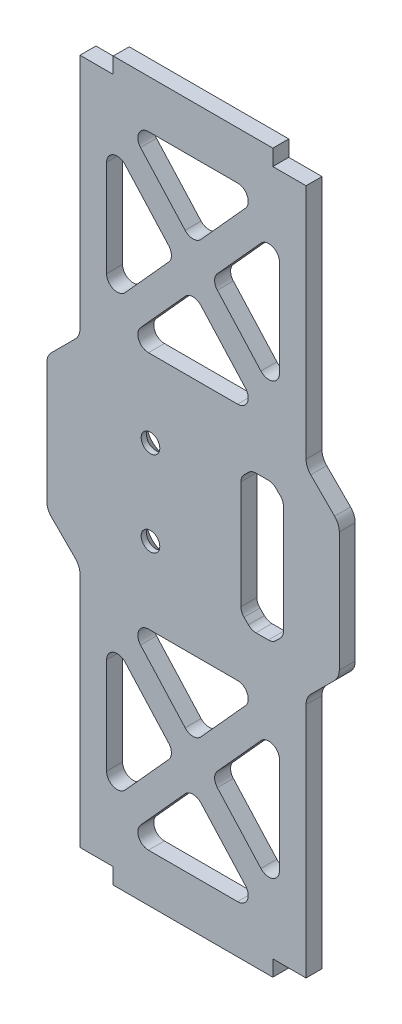
SolidWorks part; units mm, degrees
material "ABS"
ref_plane "Спереди" through (0, 0, 0) normal (0, 0, 1) x (1, 0, 0)
ref_plane "Сверху" through (0, 0, 0) normal (0, 1, 0) x (1, 0, 0)
ref_plane "Справа" through (0, 0, 0) normal (1, 0, 0) x (0, 0, -1)
sketch "Эскиз1" plane through (0, 0, 0) normal (0, 0, 1) x (1, 0, 0)
  line L0 (-27.5, 0) -> (27.5, 0) construction
  line L1 (-27.5, -64.5) -> (27.5, -64.5)
  line L2 (-27.5, -64.5) -> (-27.5, 64.5)
  line L3 (-27.5, 64.5) -> (27.5, 64.5)
  line L4 (27.5, -64.5) -> (27.5, 64.5)
  line L5 (-27.5, -64.5) -> (27.5, 64.5) construction
  line L6 (-27.5, 64.5) -> (27.5, -64.5) construction
  line L7 (-15, 61.5) -> (15, 61.5)
  line L8 (-15, 61.5) -> (-15, 67.5)
  line L9 (-15, 67.5) -> (15, 67.5)
  line L10 (15, 61.5) -> (15, 67.5)
  line L11 (-15, 61.5) -> (15, 67.5) construction
  line L12 (-15, 67.5) -> (15, 61.5) construction
  line L13 (-15, -67.5) -> (15, -61.5) construction
  line L14 (-15, -61.5) -> (15, -67.5) construction
  line L15 (15, -61.5) -> (15, -67.5)
  line L16 (-15, -67.5) -> (15, -67.5)
  line L17 (-15, -61.5) -> (-15, -67.5)
  line L18 (-15, -61.5) -> (15, -61.5)
  point P0 (0, 0)
  point P6 (0, 64.5)
  point P17 (0, -64.5)
  dimension "D1" = 3
  dimension "D2" = 30
  dimension "D3" = 12.5
  dimension "D4" = 129
extrude "Бобышка-Вытянуть1" add sketch "Эскиз1" along normal blind 3 contours L10 L7 L8 L3 L2 L1 L4 | L7 L10 L3 L8 | L3 L10 L9 L8 | L18 L17 L1 L15 | L1 L17 L16 L15
sketch "Эскиз2" plane through (0, 0, 3) normal (0, 0, 1) x (1, 0, 0)
  line L0 (-8, -64.5) -> (-8, 48.9753) construction
  line L1 (-27.5, -64.5) -> (-15, -64.5) construction
  line L2 (0, 0) -> (-27.5, 0) construction
  line L3 (-27.5, -64.5) -> (-27.5, 64.5) construction
  circle A0 centre (-8, 8) radius 1.75
  circle A1 centre (-8, -8) radius 1.75
  dimension "D1" = 3.5
  dimension "D2" = 8
  dimension "D3" = 8
extrude "Вырез-Вытянуть1" cut sketch "Эскиз2" against normal blind 10
sketch "Эскиз3" plane through (0, 0, 3) normal (0, 0, 1) x (1, 0, 0)
  line L0 (-21.25, 64.5) -> (-21.25, 18.75)
  line L1 (-27.5, 64.5) -> (-15, 64.5) construction
  line L2 (-21.25, 18.75) -> (-27.5, 12.5)
  line L3 (-27.5, -64.5) -> (-27.5, 64.5) construction
  line L4 (-27.5, 0) -> (27.5, 0) construction
  line L5 (27.5, -64.5) -> (27.5, 64.5) construction
  line L6 (0, 67.5) -> (0, -67.5) construction
  line L7 (-15, 67.5) -> (15, 67.5) construction
  line L8 (-15, -67.5) -> (15, -67.5) construction
  line L9 (-21.25, 64.5) -> (-37.5319, 71.3874)
  line L10 (-37.5319, 71.3874) -> (-35.5629, 12.5)
  line L11 (-35.5629, 12.5) -> (-27.5, 12.5)
  line L12 (35.5629, 12.5) -> (27.5, 12.5)
  line L13 (37.5319, 71.3874) -> (35.5629, 12.5)
  line L14 (21.25, 64.5) -> (37.5319, 71.3874)
  line L15 (21.25, 18.75) -> (27.5, 12.5)
  line L16 (21.25, 64.5) -> (21.25, 18.75)
  line L17 (21.25, -64.5) -> (21.25, -18.75)
  line L18 (21.25, -18.75) -> (27.5, -12.5)
  line L19 (21.25, -64.5) -> (37.5319, -71.3874)
  line L20 (37.5319, -71.3874) -> (35.5629, -12.5)
  line L21 (35.5629, -12.5) -> (27.5, -12.5)
  line L22 (-35.5629, -12.5) -> (-27.5, -12.5)
  line L23 (-37.5319, -71.3874) -> (-35.5629, -12.5)
  line L24 (-21.25, -64.5) -> (-37.5319, -71.3874)
  line L25 (-21.25, -18.75) -> (-27.5, -12.5)
  line L26 (-21.25, -64.5) -> (-21.25, -18.75)
  dimension "D1" = 135
  dimension "D2" = 12.5
extrude "Вырез-Вытянуть2" cut sketch "Эскиз3" against normal blind 10
fillet "Скругление1" radius 3 8 edges at (-21.25, -18.75, 1.5) (-27.5, -12.5, 1.5) (-27.5, 12.5, 1.5) (-21.25, 18.75, 1.5) (27.5, 12.5, 1.5) (21.25, 18.75, 1.5) (27.5, -12.5, 1.5) (21.25, -18.75, 1.5)
chamfer "Фаска1" distance 2 angle 45 2 edges at (-6.25, -8, 0) (-6.25, 8, 0)
sketch "Эскиз4" plane through (0, 0, 3) normal (0, 0, 1) x (1, 0, 0)
  line L0 (27.5, 0) -> (-27.5, 0) construction
  line L1 (27.5, -11.2574) -> (27.5, 11.2574) construction
  line L2 (-27.5, -11.2574) -> (-27.5, 11.2574) construction
  line L3 (0, 67.5) -> (0, -67.5) construction
  line L4 (-15, 67.5) -> (15, 67.5) construction
  line L5 (-15, -67.5) -> (15, -67.5) construction
  line L6 (-21.25, 19.9926) -> (-21.25, 64.5) construction
  line L7 (-16.25, 58.5) -> (16.25, 58.5)
  line L8 (-16.25, 58.5) -> (-16.25, 22.5)
  line L9 (-16.25, 22.5) -> (16.25, 22.5)
  line L10 (16.25, 58.5) -> (16.25, 22.5)
  line L11 (-16.25, 58.5) -> (16.25, 22.5) construction
  line L12 (-16.25, 22.5) -> (16.25, 58.5) construction
  line L13 (-21.25, 64.5) -> (-15, 64.5) construction
  line L14 (-16.25, 54.7692) -> (12.8819, 22.5)
  line L15 (-12.8819, 58.5) -> (16.25, 26.2308)
  line L16 (-12.8819, 22.5) -> (16.25, 54.7692)
  line L17 (-16.25, 26.2308) -> (12.8819, 58.5)
  line L18 (-14.3943, 60.1753) -> (18.1057, 24.1753) construction
  line L19 (-18.1057, 56.8247) -> (14.3943, 20.8247) construction
  line L20 (-18.1057, 24.1753) -> (14.3943, 60.1753) construction
  line L21 (-14.3943, 20.8247) -> (18.1057, 56.8247) construction
  line L22 (-16.25, -22.5) -> (16.25, -58.5) construction
  line L23 (-16.25, -58.5) -> (16.25, -22.5) construction
  line L24 (-16.25, -26.2308) -> (12.8819, -58.5)
  line L25 (-12.8819, -22.5) -> (16.25, -54.7692)
  line L26 (-12.8819, -58.5) -> (16.25, -26.2308)
  line L27 (-16.25, -54.7692) -> (12.8819, -22.5)
  line L28 (16.25, -58.5) -> (16.25, -22.5)
  line L29 (-16.25, -22.5) -> (16.25, -22.5)
  line L30 (-16.25, -58.5) -> (-16.25, -22.5)
  line L31 (-16.25, -58.5) -> (16.25, -58.5)
  line L32 (13, 19.2917) -> (13, -16.8497) construction
  line L33 (15, 13) -> (11, 13)
  line L34 (11, 13) -> (9, 11)
  line L35 (9, 11) -> (9, -11)
  line L36 (17, 11) -> (17, -11)
  line L37 (15, 13) -> (17, 11)
  line L38 (15, -13) -> (17, -11)
  line L39 (11, -13) -> (9, -11)
  line L40 (15, -13) -> (11, -13)
  point P12 (0, 40.5)
  point P49 (0, -40.5)
  point P59 (13, 13)
  point P61 (17, 0)
  point P62 (9, 0)
  point P63 (13, -13)
  dimension "D1" = 5
  dimension "D2" = 6
  dimension "D3" = 36
  dimension "D8" = 135
  dimension "D9" = 4
  dimension "D10" = 13
  dimension "D11" = 13
  dimension "D12" = 2
  dimension "D4" = 2.5
  dimension "D5" = 2.5
  dimension "D6" = 2.5
  dimension "D7" = 2.5
extrude "Вырез-Вытянуть3" cut sketch "Эскиз4" against normal blind 10 contours L16 L9 L14 | L8 L17 L14 | L15 L17 L7 | L16 L15 L10 | L40 L38 L36 L37 L33 L34 L35 L39 | L29 L25 L27 | L25 L28 L26 | L26 L31 L24 | L30 L27 L24
fillet "Скругление2" radius 2 32 edges at (16.25, -26.2308, 1.5) (3.3681, -40.5, 1.5) (16.25, -54.7692, 1.5) (12.8819, -58.5, 1.5) (-12.8819, -58.5, 1.5) (0, -44.2308, 1.5) (-3.3681, -40.5, 1.5) (-16.25, -54.7692, 1.5) (-16.25, -26.2308, 1.5) (-12.8819, -22.5, 1.5) (12.8819, -22.5, 1.5) (0, -36.7692, 1.5) (17, -11, 1.5) (15, -13, 1.5) (11, -13, 1.5) (9, -11, 1.5) (9, 11, 1.5) (17, 11, 1.5) (15, 13, 1.5) (11, 13, 1.5) (12.8819, 22.5, 1.5) (-12.8819, 22.5, 1.5) (-16.25, 54.7692, 1.5) (-16.25, 26.2308, 1.5) (-3.3681, 40.5, 1.5) (3.3681, 40.5, 1.5) (16.25, 26.2308, 1.5) (16.25, 54.7692, 1.5) (12.8819, 58.5, 1.5) (0, 44.2308, 1.5) (-12.8819, 58.5, 1.5) (0, 36.7692, 1.5)
